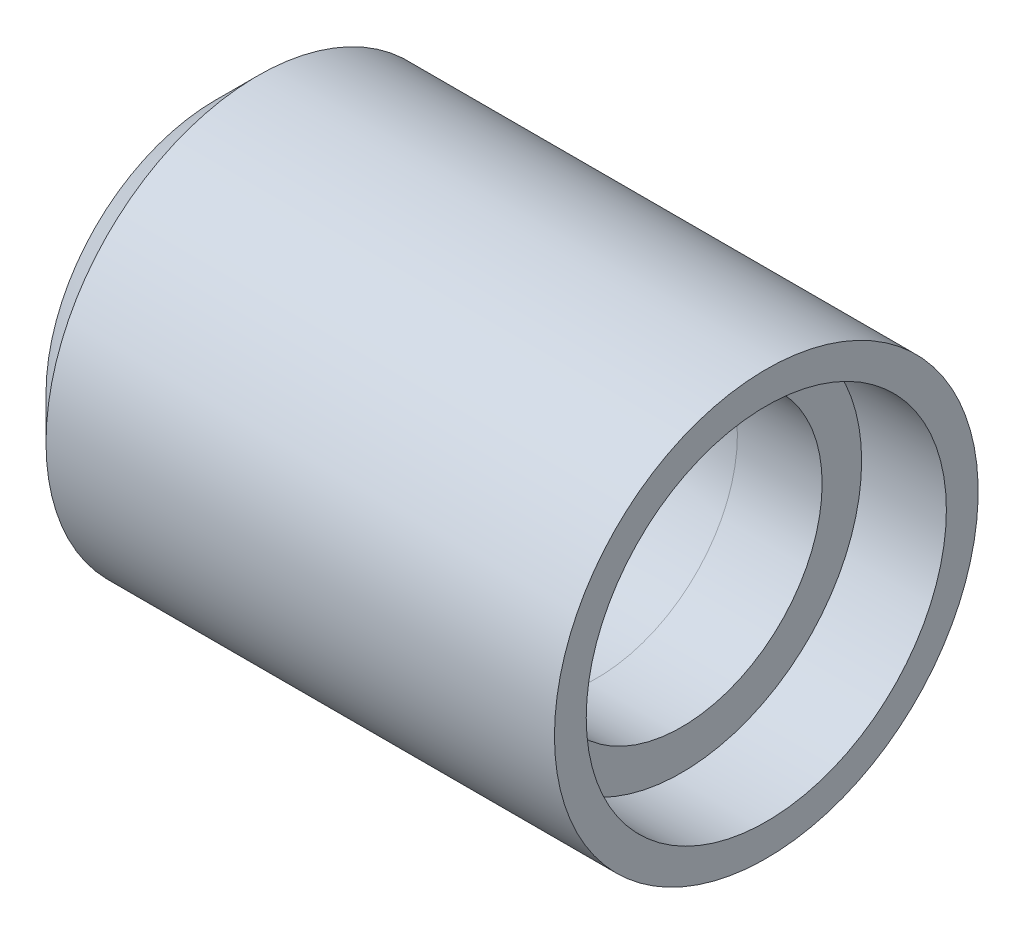
SolidWorks part; units mm, degrees
ref_plane "Front Plane" through (0, 0, 0) normal (0, 0, 1) x (1, 0, 0)
ref_plane "Top Plane" through (0, 0, 0) normal (0, 1, 0) x (1, 0, 0)
ref_plane "Right Plane" through (0, 0, 0) normal (1, 0, 0) x (0, 0, -1)
sketch "Sketch1" plane through (0, 0, 0) normal (0, 0, 1) x (1, 0, 0)
  line L1 (1, 5) -> (13, 5)
  line L3 (11, 3.3176) -> (9, 3.3176)
  line L7 (9, 3.3176) -> (1.2, 4)
  line L8 (1.2, 4) -> (1.2, 3)
  line L9 (1.2, 3) -> (0.5, 3)
  line L10 (0, 0) -> (18.1228, 0) construction
  line L13 (0, 3.5) -> (0, 4)
  line L14 (11, 3.3176) -> (11, 4.25)
  line L15 (11, 4.25) -> (13, 4.25)
  line L16 (13, 4.25) -> (13, 5)
  line L17 (0, 4) -> (1, 5)
  line L18 (0, 3.5) -> (0.5, 3.5)
  line L19 (0.5, 3.5) -> (0.5, 3)
  point P15 (0, 0)
  point P16 (0, 0)
  dimension "D1" = 10
  dimension "D2" = 6
  dimension "D3" = 8
  dimension "D4" = 5
  dimension "D5" = 7.8
  dimension "D6" = 8.5
  dimension "D7" = 1
  dimension "D8" = 2
  dimension "D9" = 2
  dimension "D10" = 45
  dimension "D11" = 1.2
  dimension "D12" = 0.5
revolve "Revolve1" add sketch "Sketch1" angle 360 about L10
